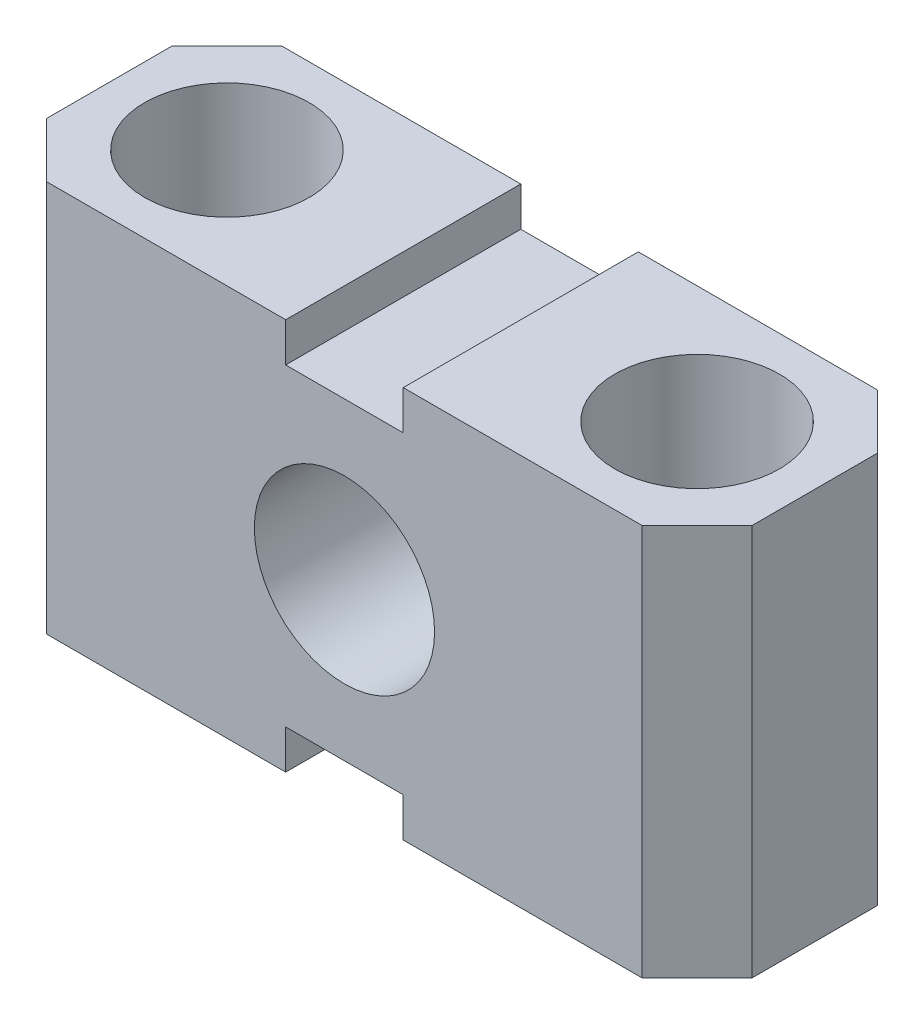
SolidWorks part; units mm, degrees
ref_plane "前视基准面" through (0, 0, 0) normal (0, 0, 1) x (1, 0, 0)
ref_plane "上视基准面" through (0, 0, 0) normal (0, 1, 0) x (1, 0, 0)
ref_plane "右视基准面" through (0, 0, 0) normal (1, 0, 0) x (0, 0, -1)
sketch "草图1" plane through (0, 0, 0) normal (0, 0, 1) x (1, 0, 0)
  line L1 (0, 0) -> (90, 0)
  line L2 (0, 0) -> (0, -50)
  line L3 (0, -50) -> (90, -50)
  line L4 (90, 0) -> (90, -50)
  dimension "D1" = 90
  dimension "D2" = 50
extrude "拉伸1" add sketch "草图1" along normal blind 30
sketch "草图3" plane through (0, 0, 0) normal (0, 1, 0) x (1, 0, 0)
  line L0 (90, -30) -> (0, -30) construction
  line L1 (90, 0) -> (0, 0) construction
  line L2 (90, -30) -> (90, 0) construction
  line L3 (0, -30) -> (0, 0) construction
  circle A0 centre (15, -15) radius 10.5
  circle A1 centre (75, -15) radius 10.5
  dimension "D3" = 15
  dimension "D1" = 15
  dimension "D2" = 15
  dimension "D4" = 15
  dimension "D5" = 21
extrude "切除-拉伸2" cut sketch "草图3" against normal through all
chamfer "倒角1" distance 7 angle 45 4 edges at (90, -25, 0) (90, -25, 30) (0, -25, 30) (0, -25, 0)
sketch "草图7" plane through (0, 0, 30) normal (0, 0, 1) x (1, 0, 0)
  line L1 (83, 0) -> (7, 0) construction
  line L2 (90, 0) -> (90, -50) construction
  circle A0 centre (45, -25) radius 11.5
  dimension "D1" = 25
  dimension "D2" = 23
  dimension "D3" = 45
sketch "草图8" plane through (0, 0, 0) normal (0, 0, -1) x (-1, 0, 0)
  line L2 (-83, 0) -> (-7, 0) construction
  line L3 (-90, -50) -> (-90, 0) construction
  circle A0 centre (-45, -25) radius 18
  dimension "D1" = 36
  dimension "D2" = 25
  dimension "D3" = 45
extrude "切除-拉伸5" cut sketch "草图8" against normal blind 2
extrude "切除-拉伸6" cut sketch "草图7" against normal blind 120
sketch "草图12" plane through (0, 0, 0) normal (0, 0, -1) x (-1, 0, 0)
  line L0 (-83, 0) -> (-7, 0) construction
  line L1 (-52.5, 0) -> (-37.5, 0)
  line L2 (-52.5, 0) -> (-52.5, -5)
  line L3 (-52.5, -5) -> (-37.5, -5)
  line L4 (-37.5, 0) -> (-37.5, -5)
  line L5 (-37.5, -50) -> (-37.5, -45)
  line L7 (-52.5, -45) -> (-37.5, -45)
  line L8 (-52.5, -50) -> (-52.5, -45)
  line L9 (-52.5, -50) -> (-37.5, -50)
  dimension "D1" = 5
  dimension "D3" = 5
extrude "切除-拉伸8" cut sketch "草图12" against normal blind 70
